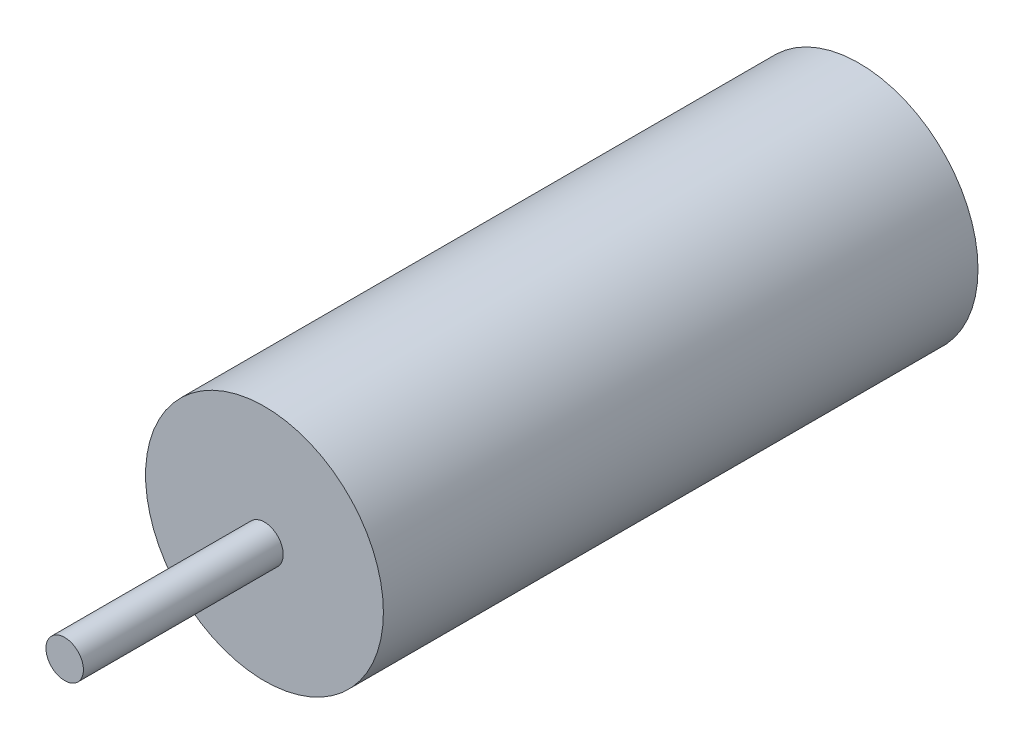
SolidWorks part; units mm, degrees
ref_plane "Front Plane" through (0, 0, 0) normal (0, 0, 1) x (1, 0, 0)
ref_plane "Top Plane" through (0, 0, 0) normal (0, 1, 0) x (1, 0, 0)
ref_plane "Right Plane" through (0, 0, 0) normal (1, 0, 0) x (0, 0, -1)
sketch "Sketch1" plane through (0, 0, 0) normal (0, 0, 1) x (1, 0, 0)
  circle A0 centre (0, 0) radius 25.4
  dimension "D1" = 50.8
extrude "Boss-Extrude1" add sketch "Sketch1" along normal blind 127
sketch "Sketch2" plane through (0, 0, 127) normal (0, 0, 1) x (1, 0, 0)
  circle A0 centre (0, 0) radius 4.0005
  dimension "D1" = 8.001
extrude "Boss-Extrude2" add sketch "Sketch2" along normal blind 42.672
